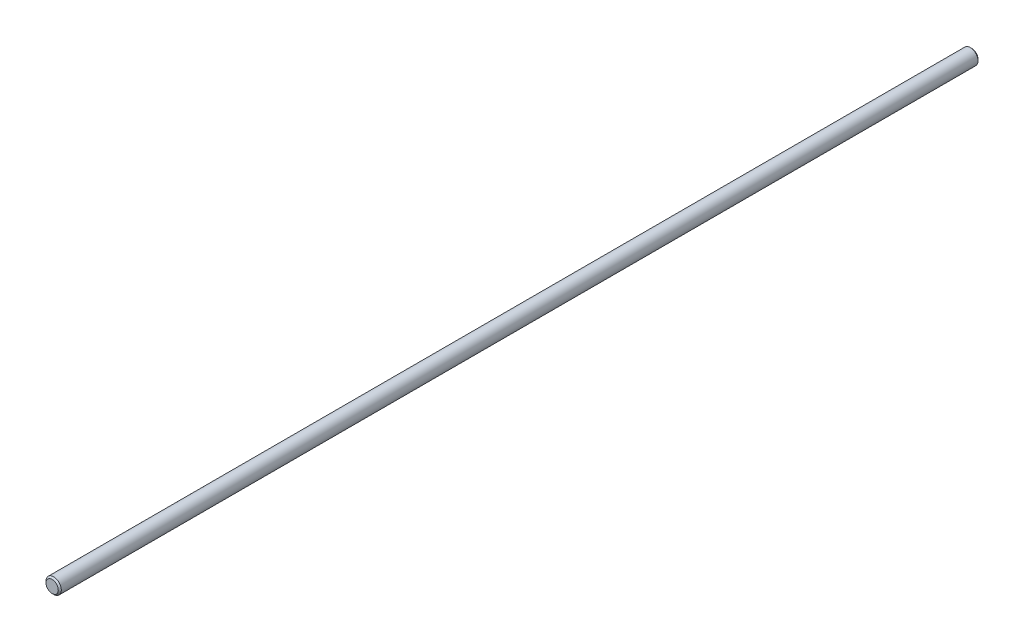
SolidWorks part; units mm, degrees
material "Plain Carbon Steel"
ref_plane "Front Plane" through (0, 0, 0) normal (0, 0, 1) x (1, 0, 0)
ref_plane "Top Plane" through (0, 0, 0) normal (0, 1, 0) x (1, 0, 0)
ref_plane "Right Plane" through (0, 0, 0) normal (1, 0, 0) x (0, 0, -1)
sketch "Sketch1" plane through (0, 0, 0) normal (0, 0, 1) x (1, 0, 0)
  circle A0 centre (0, 0) radius 12.7
  dimension "D1" = 25.4
extrude "Boss-Extrude1" add sketch "Sketch1" along normal mid plane 1524
chamfer "Chamfer1" distance 2.54 angle 45 2 edges at (12.7, 0, -762) (12.7, 0, 762)
